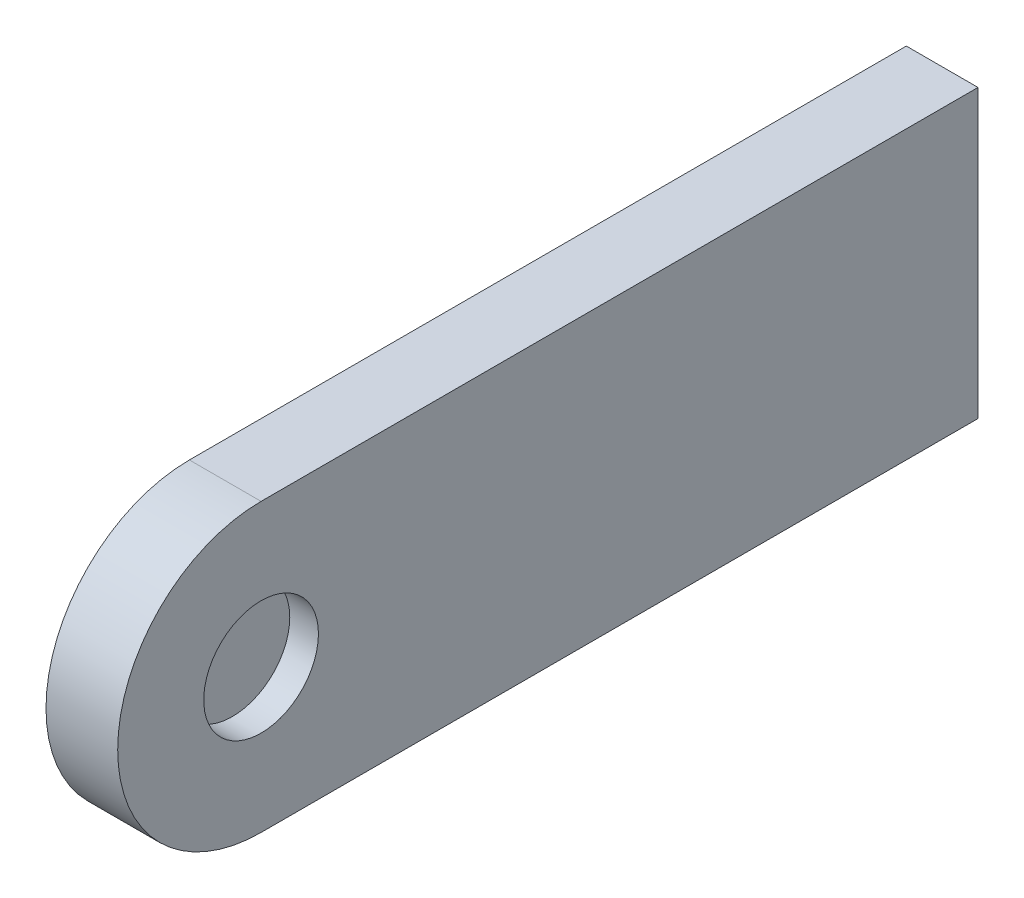
SolidWorks part; units mm, degrees
ref_plane "Front Plane" through (0, 0, 0) normal (0, 0, 1) x (1, 0, 0)
ref_plane "Top Plane" through (0, 0, 0) normal (0, 1, 0) x (1, 0, 0)
ref_plane "Right Plane" through (0, 0, 0) normal (1, 0, 0) x (0, 0, -1)
sketch "Sketch1" plane through (0, 0, 0) normal (1, 0, 0) x (0, 0, -1)
  line L1 (-25, 10) -> (25, 10)
  line L3 (-25, -10) -> (25, -10)
  line L4 (25, 10) -> (25, -10)
  arc A0 (-25, 10) -> (-25, -10) centre (-25, 0) ccw
  point P0 (0, 0)
  dimension "D1" = 20
  dimension "D2" = 50
extrude "Boss-Extrude1" add sketch "Sketch1" along normal blind 5
sketch "Sketch2" plane through (5, 0, 0) normal (1, 0, 0) x (0, 0, -1)
  line L0 (-25, 10) -> (-25, -10)
  arc A0 (-25, 10) -> (-25, -10) centre (-25, 0) ccw construction
  circle A1 centre (-25, 0) radius 4
  dimension "D1" = 8
  dimension "D2" = 8
extrude "Cut-Extrude3" cut sketch "Sketch2" against normal blind 2 contours L0 A1 | L0 A1
